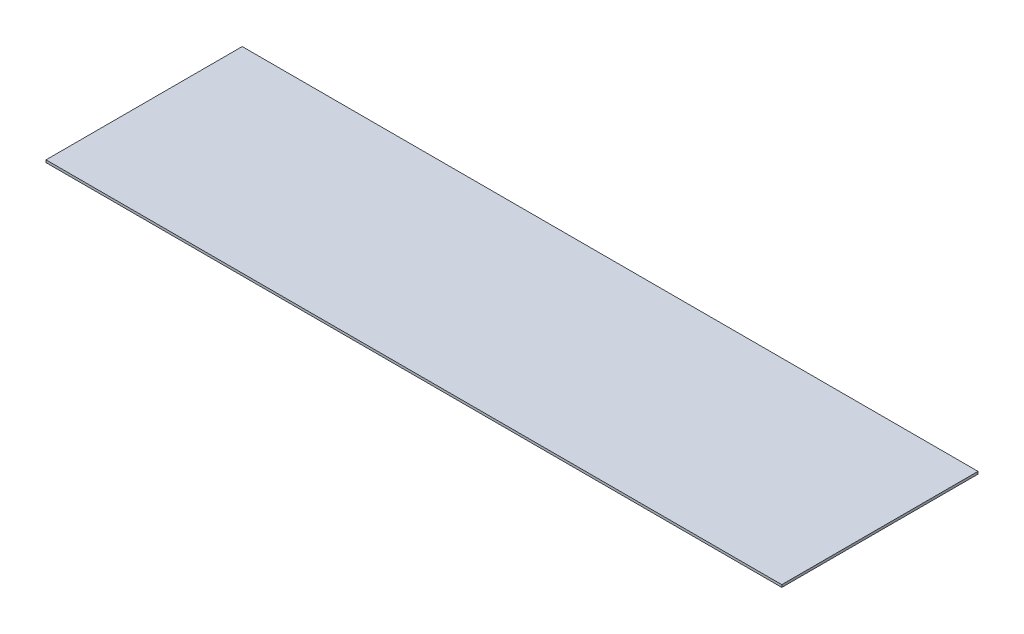
SolidWorks part; units mm, degrees
ref_plane "Front Plane" through (0, 0, 0) normal (0, 0, 1) x (1, 0, 0)
ref_plane "Top Plane" through (0, 0, 0) normal (0, 1, 0) x (1, 0, 0)
ref_plane "Right Plane" through (0, 0, 0) normal (1, 0, 0) x (0, 0, -1)
sketch "Sketch1" plane through (0, 0, 0) normal (0, 1, 0) x (1, 0, 0)
  line L1 (-750, 200) -> (750, 200)
  line L2 (-750, 200) -> (-750, -200)
  line L3 (-750, -200) -> (750, -200)
  line L4 (750, 200) -> (750, -200)
  line L5 (-750, 200) -> (750, -200) construction
  line L6 (-750, -200) -> (750, 200) construction
  point P0 (0, 0)
  dimension "D1" = 400
  dimension "D2" = 1500
extrude "Boss-Extrude1" add sketch "Sketch1" along normal mid plane 5
